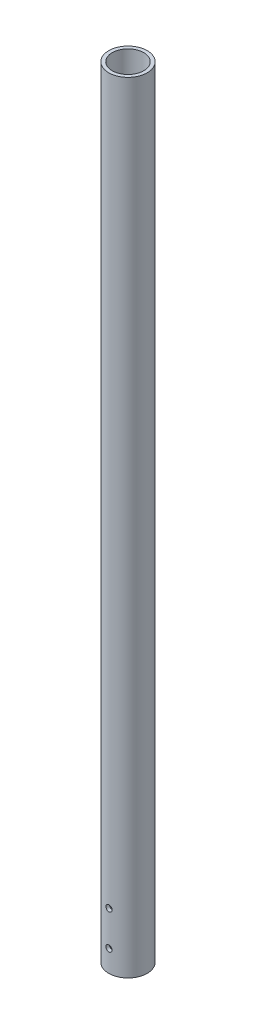
SolidWorks part; units mm, degrees
ref_plane "Front Plane" through (0, 0, 0) normal (0, 0, 1) x (1, 0, 0)
ref_plane "Top Plane" through (0, 0, 0) normal (0, 1, 0) x (1, 0, 0)
ref_plane "Right Plane" through (0, 0, 0) normal (1, 0, 0) x (0, 0, -1)
sketch "Sketch1" plane through (0, 0, 0) normal (0, 1, 0) x (1, 0, 0)
  circle A0 centre (0, 0) radius 21.082
  circle A1 centre (0, 0) radius 17.272
  dimension "D1" = 34.544
  dimension "1.66" = 42.164
extrude "Boss-Extrude1" add sketch "Sketch1" along normal blind 855.6625
ref_plane "Plane1" through (0, 0, 21.082) normal (0, 0, 1) x (1, 0, 0)
sketch "Sketch2" plane through (0, 0, 21.082) normal (0, 0, 1) x (1, 0, 0)
  line L0 (-21.082, 1.5875) -> (21.082, 1.5875) construction
  line L1 (-21.082, 855.6625) -> (-21.082, 0) construction
  line L2 (-21.082, 0) -> (21.082, 0) construction
  line L3 (-21.082, 103.1875) -> (21.082, 103.1875) construction
  line L4 (21.082, 0) -> (21.082, 855.6625) construction
  point P0 (0, 23.8125)
  point P1 (0, 61.9125)
  dimension "D1" = 1.5875
  dimension "D2" = 23.8125
  dimension "D3" = 38.1
  dimension "D4" = 101.6
hole_wizard "1/4 Clearance Hole1" positions "Sketch3" profile "Sketch4" hole size "1/4" standard "ANSI Inch" end condition through all
sketch "Sketch3" plane through (0, 0, 21.082) normal (0, 0, 1) x (1, 0, 0)
  point P0 (0, 23.8125)
  point P3 (0, 61.9125)
sketch "Sketch4" plane through (0, 23.8125, 21.082) normal (1, 0, 0) x (0, -1, 0)
  line L0 (0, 0) -> (0, 42.164)
  line L1 (0, 42.164) -> (3.3782, 42.164)
  line L2 (3.3782, 42.164) -> (3.3782, 0)
  line L5 (3.3782, 0) -> (0, 0)
  line L11 (0, -6.35) -> (0, 107.95) construction
  dimension "Thru Hole Dia." = 6.7564
  dimension "Thru Hole Depth" = 42.164
